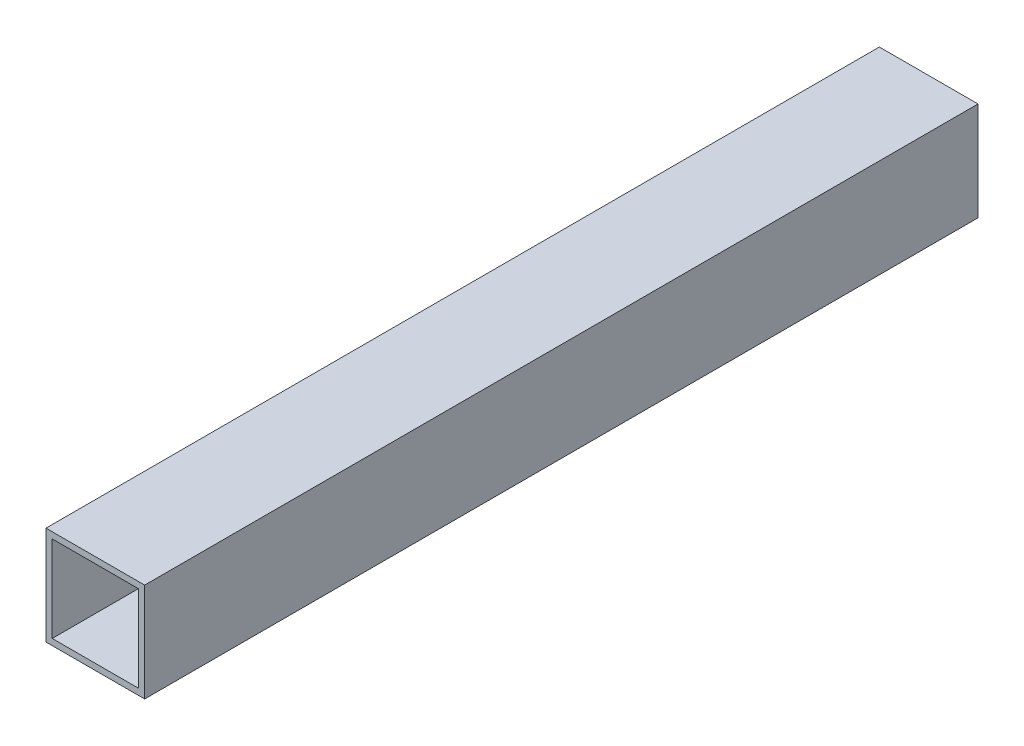
SolidWorks part; units mm, degrees
ref_plane "Front Plane" through (0, 0, 0) normal (0, 0, 1) x (1, 0, 0)
ref_plane "Top Plane" through (0, 0, 0) normal (0, 1, 0) x (1, 0, 0)
ref_plane "Right Plane" through (0, 0, 0) normal (1, 0, 0) x (0, 0, -1)
sketch "Sketch1" plane through (0, 0, 0) normal (0, 0, 1) x (1, 0, 0)
  line L0 (8.3, 8.3) -> (8.3, -8.3)
  line L1 (9.5, 9.5) -> (-9.5, 9.5)
  line L2 (9.5, 9.5) -> (9.5, -9.5)
  line L3 (9.5, -9.5) -> (-9.5, -9.5)
  line L4 (-9.5, 9.5) -> (-9.5, -9.5)
  line L5 (9.5, 9.5) -> (-9.5, -9.5) construction
  line L6 (9.5, -9.5) -> (-9.5, 9.5) construction
  line L7 (8.3, -8.3) -> (-8.3, -8.3)
  line L8 (-8.3, 8.3) -> (-8.3, -8.3)
  line L9 (8.3, 8.3) -> (-8.3, 8.3)
  point P0 (0, 0)
  dimension "D1" = 19
  dimension "D2" = 1.2
extrude "Boss-Extrude1" add sketch "Sketch1" along normal mid plane 160.5
